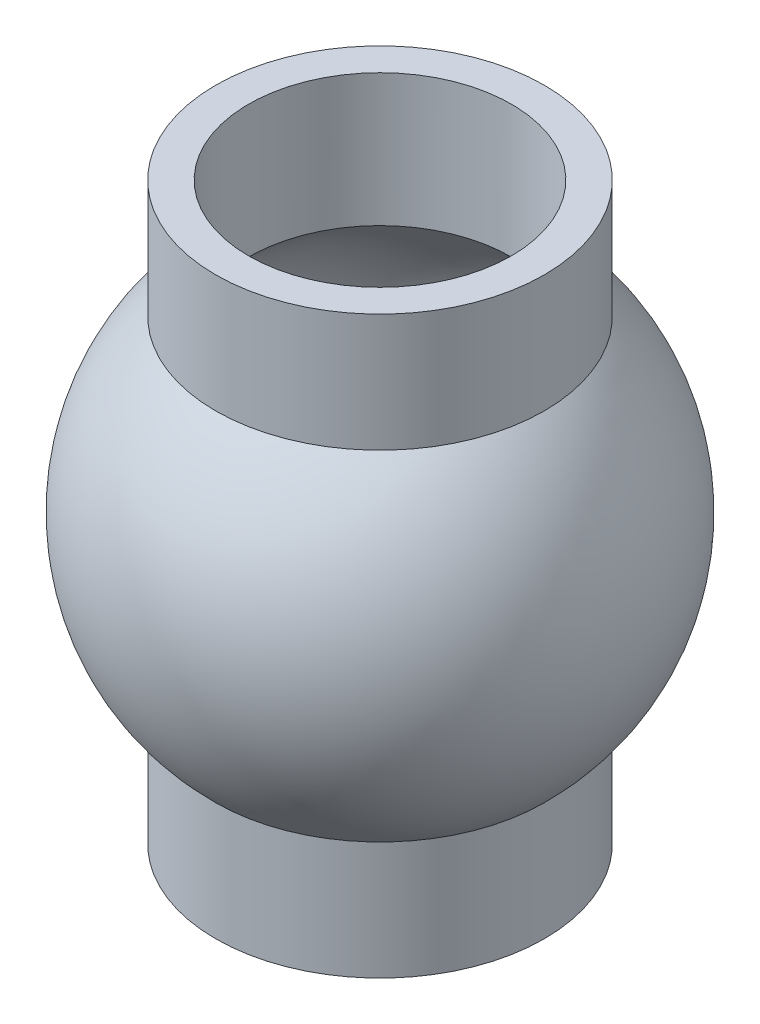
SolidWorks part; units mm, degrees
ref_plane "Front Plane" through (0, 0, 0) normal (0, 0, 1) x (1, 0, 0)
ref_plane "Top Plane" through (0, 0, 0) normal (0, 1, 0) x (1, 0, 0)
ref_plane "Right Plane" through (0, 0, 0) normal (1, 0, 0) x (0, 0, -1)
ref_axis "Axis1" through (0, 55, 0) along (0, -1, 0)
sketch "Sketch1" plane through (0, 0, 0) normal (0, 0, 1) x (1, 0, 0)
  line L1 (0, -2.875) -> (0, 2.875)
  arc A0 (0, 2.875) -> (0, -2.875) centre (0, 0) ccw
  dimension "D1" = 5.75
revolve "Revolve1" add sketch "Sketch1" angle 360 about axis through (0, 55, 0) along (0, -1, 0)
sketch "Sketch2" plane through (0, 0, 0) normal (0, 1, 0) x (1, 0, 0)
  circle A0 centre (0, 0) radius 2
  dimension "D1" = 4
extrude "Boss-Extrude1" add sketch "Sketch2" along normal mid plane 7
shell "Shell1" thickness 0.4
